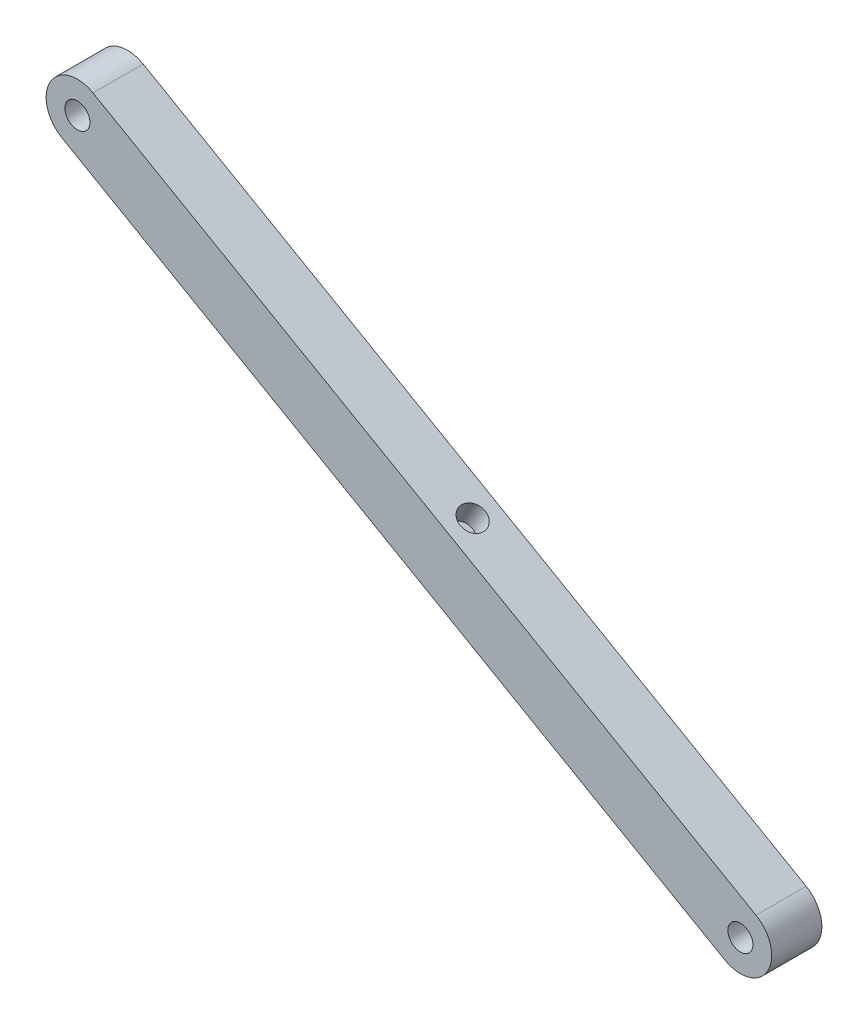
SolidWorks part; units mm, degrees
ref_plane "Спереди" through (0, 0, 0) normal (0, 0, 1) x (1, 0, 0)
ref_plane "Сверху" through (0, 0, 0) normal (0, 1, 0) x (1, 0, 0)
ref_plane "Справа" through (0, 0, 0) normal (1, 0, 0) x (0, 0, -1)
sketch "Sketch1" plane through (0, 0, 0) normal (0, 0, 1) x (1, 0, 0)
  line L0 (-5.265, 31.0446) -> (-58.1685, 61.4127) construction
  line L5 (-58.1685, 61.4127) -> (-5.265, 31.0446) construction
  line L6 (-56.9239, 63.5809) -> (-4.0204, 33.2128)
  line L7 (-59.4131, 59.2445) -> (-6.5096, 28.8765)
  arc A2 (-56.9239, 63.5809) -> (-59.4131, 59.2445) centre (-58.1685, 61.4127) ccw
  arc A3 (-6.5096, 28.8765) -> (-4.0204, 33.2128) centre (-5.265, 31.0446) ccw
  circle A4 centre (-58.1685, 61.4127) radius 1
  circle A5 centre (-5.265, 31.0446) radius 1
  point P2 (-31.7167, 46.2287)
  dimension "D3" = 2
  dimension "D1" = 61
  dimension "D2" = 5
extrude "Boss-Extrude1" add sketch "Sketch1" along normal blind 4
sketch "Sketch2" plane through (13.3435, 23.2454, 0) normal (0.4978, 0.8673, 0) x (0.8673, -0.4978, 0)
  line L0 (-50.3436, -2) -> (-46.6778, -2) construction
  line L2 (-48.4037, -4) -> (-48.4037, 0) construction
  circle A0 centre (-48.4037, -2) radius 1
  dimension "D1" = 2
extrude "Cut-Extrude1" cut sketch "Sketch2" against normal blind 2
